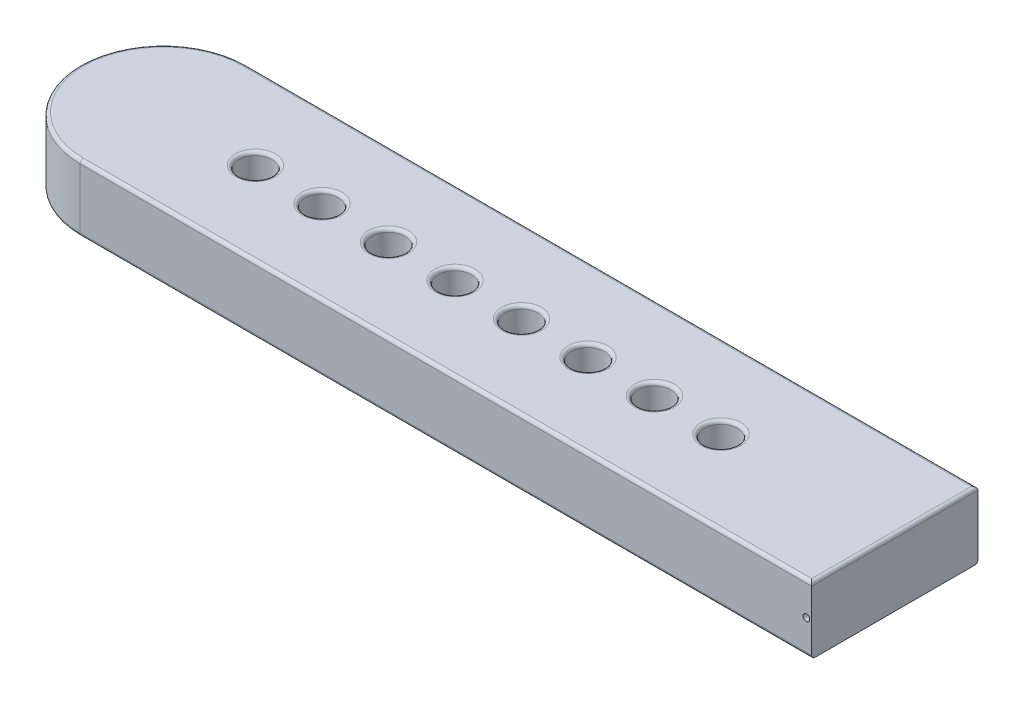
SolidWorks part; units mm, degrees
ref_plane "Alzado" through (0, 0, 0) normal (0, 0, 1) x (1, 0, 0)
ref_plane "Planta" through (0, 0, 0) normal (0, 1, 0) x (1, 0, 0)
ref_plane "Vista lateral" through (0, 0, 0) normal (1, 0, 0) x (0, 0, -1)
sketch "Croquis1" plane through (0, 0, 0) normal (0, 1, 0) x (1, 0, 0)
  line L0 (0, 2.5) -> (-11, 2.5)
  line L2 (-11, 0) -> (0, 0)
  line L3 (0, 0) -> (0, 2.5)
  arc A1 (-11, 2.5) -> (-11, 0) centre (-11, 1.25) ccw
  circle A2 centre (-9.6151, 1.25) radius 0.25
  circle A3 centre (-8.6151, 1.25) radius 0.25
  circle A4 centre (-7.6151, 1.25) radius 0.25
  circle A5 centre (-6.6151, 1.25) radius 0.25
  circle A6 centre (-5.6151, 1.25) radius 0.25
  circle A7 centre (-4.6151, 1.25) radius 0.25
  circle A8 centre (-3.6151, 1.25) radius 0.25
  circle A9 centre (-2.6151, 1.25) radius 0.25
  dimension "D3" = 0
  dimension "D4" = 0.5
  dimension "D1" = 11
  dimension "D2" = 2.5
  dimension "D5" = 8
extrude "Saliente-Extruir1" add sketch "Croquis1" along normal blind 1
fillet "Redondeo2" radius 0.05 23 edges at (-5.5, 0, -2.5) (-12.25, 0, -1.25) (-2.6151, 1, -1) (-4.6151, 1, -1) (-6.6151, 1, -1) (-8.6151, 1, -1) (-5.5, 1, 0) (-12.25, 1, -1.25) (-5.5, 1, -2.5) (0, 1, -1.25) (-9.6151, 1, -1) (-7.6151, 1, -1) (-5.6151, 1, -1) (-3.6151, 1, -1) (-5.5, 0, 0) (-9.6151, 0, -1) (-8.6151, 0, -1) (-7.6151, 0, -1) (-6.6151, 0, -1) (-5.6151, 0, -1) (-4.6151, 0, -1) (-2.6151, 0, -1) (-3.6151, 0, -1)
sketch "Croquis2" plane through (0, 0, 0) normal (0, 0, 1) x (1, 0, 0)
  line L0 (-11, 1) -> (-0.05, 1) construction
  line L2 (0, 0.95) -> (0, 0.05) construction
  circle A0 centre (-0.08, 0.5022) radius 0.05
  dimension "D1" = 0.4978
  dimension "D2" = 0.08
  dimension "D3" = 0.1
extrude "Cortar-Extruir1" cut sketch "Croquis2" against normal through all
